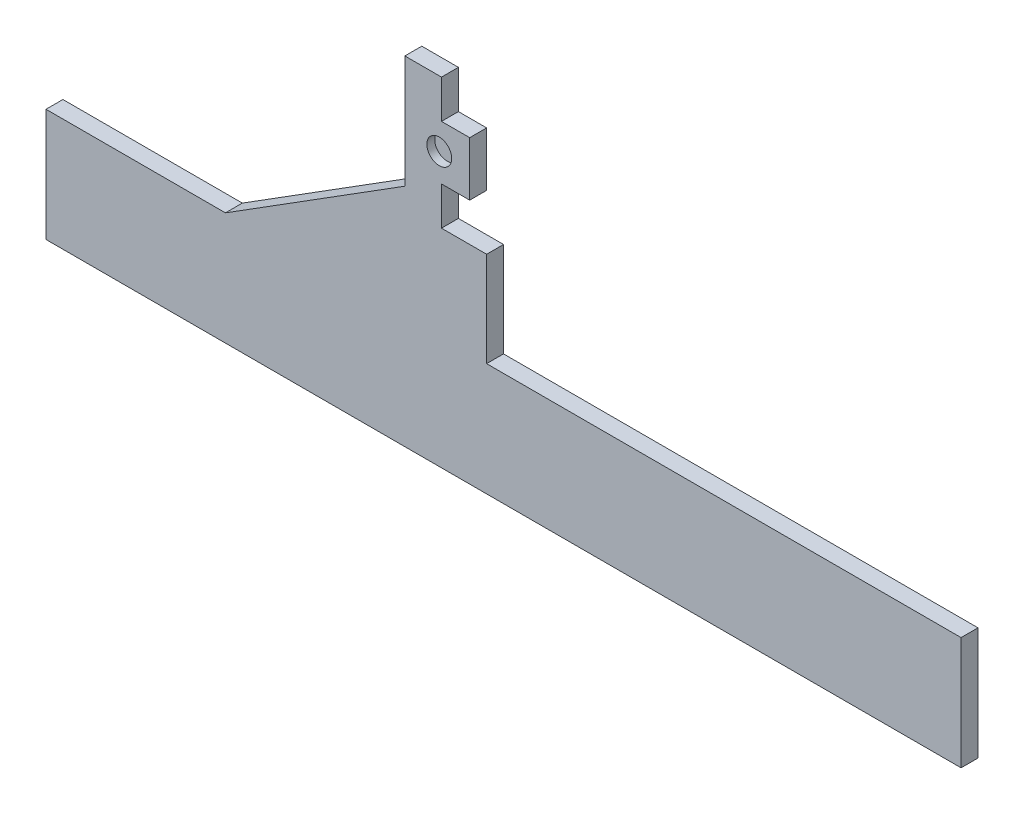
SolidWorks part; units mm, degrees
ref_plane "Alzado" through (0, 0, 0) normal (0, 0, 1) x (1, 0, 0)
ref_plane "Planta" through (0, 0, 0) normal (0, 1, 0) x (1, 0, 0)
ref_plane "Vista lateral" through (0, 0, 0) normal (1, 0, 0) x (0, 0, -1)
sketch "Croquis1" plane through (0, 0, 0) normal (0, 0, 1) x (1, 0, 0)
  line L0 (-15, 50) -> (-15, 134)
  line L1 (-405.6, -50) -> (405.6, -50)
  line L2 (-405.6, -50) -> (-405.6, 50)
  line L3 (-405.6, 50) -> (-246.54, 50)
  line L4 (405.6, -50) -> (405.6, 50)
  line L5 (-405.6, -50) -> (405.6, 50) construction
  line L6 (-405.6, 50) -> (405.6, -50) construction
  line L7 (-55, 250) -> (-87.48, 250)
  line L8 (-87.48, 250) -> (-87.48, 150)
  line L9 (-15, 50) -> (405.6, 50)
  line L10 (-87.48, 150) -> (-246.54, 50)
  line L11 (-246.54, 50) -> (-87.48, 50) construction
  line L12 (-87.48, 50) -> (-87.48, 150) construction
  line L13 (-30, 168) -> (-30, 216)
  line L16 (-30, 216) -> (-55, 216)
  line L17 (-55, 250) -> (-55, 216)
  line L18 (-15, 134) -> (-55, 134)
  line L20 (-30, 168) -> (-55, 168)
  line L21 (-55, 134) -> (-55, 168)
  point P0 (0, 0)
  dimension "D1" = 811.2
  dimension "D2" = 100
  dimension "D3" = 72.48
  dimension "D4" = 15
  dimension "D5" = 200
  dimension "D6" = 34
  dimension "D7" = 48
  dimension "D8" = 15
  dimension "D9" = 40
extrude "Saliente-Extruir1" add sketch "Croquis1" along normal blind 15
sketch "Croquis2" plane through (0, 0, 15) normal (0, 0, 1) x (1, 0, 0)
  line L0 (0, -50) -> (0, 50) construction
  line L3 (-405.6, -50) -> (405.6, -50) construction
  line L4 (405.6, 50) -> (-15, 50) construction
sketch "Croquis3" plane through (0, 50, 0) normal (0, 1, 0) x (1, 0, 0)
  line L0 (-326.07, -15) -> (-326.07, 0) construction
  line L1 (-246.54, -15) -> (-405.6, -15) construction
  line L2 (-246.54, 0) -> (-405.6, 0) construction
sketch "Croquis4" plane through (0, 0, 15) normal (0, 0, 1) x (1, 0, 0)
  line L0 (-87.48, 250) -> (-87.48, 150) construction
  line L1 (-30, 216) -> (-55, 216) construction
  circle A0 centre (-56.98, 192) radius 11
  dimension "D1" = 22
  dimension "D2" = 30.5
  dimension "D3" = 24
extrude "Cortar-Extruir1" cut sketch "Croquis4" against normal blind 7
